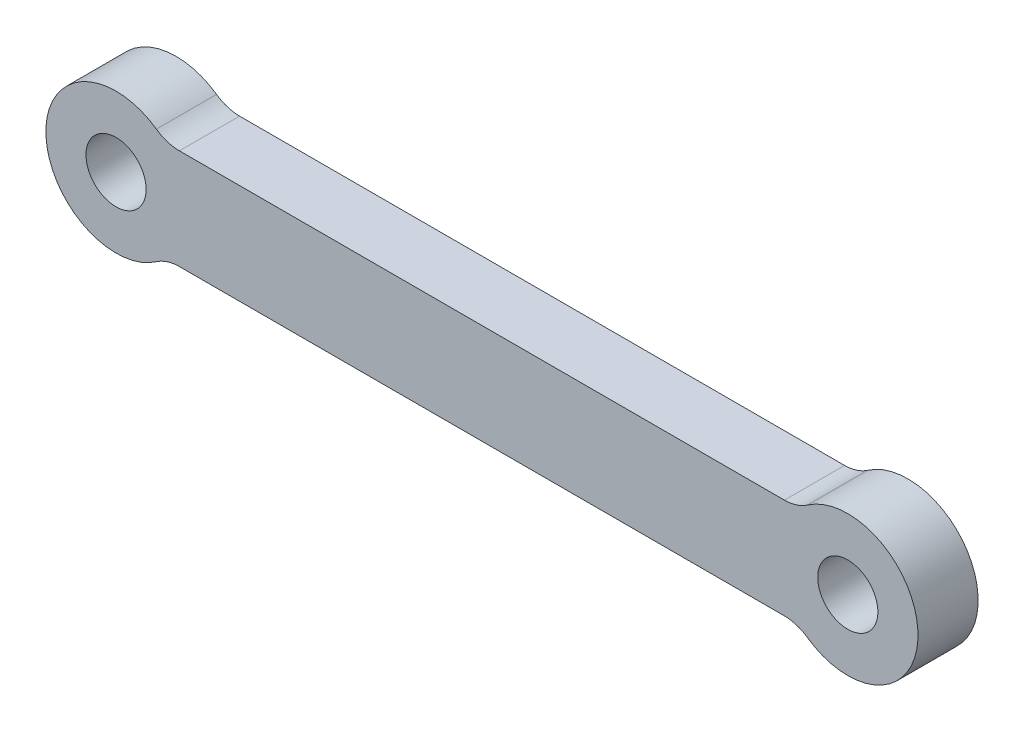
SolidWorks part; units mm, degrees
ref_plane "前视基准面" through (0, 0, 0) normal (0, 0, 1) x (1, 0, 0)
ref_plane "上视基准面" through (0, 0, 0) normal (0, 1, 0) x (1, 0, 0)
ref_plane "右视基准面" through (0, 0, 0) normal (1, 0, 0) x (0, 0, -1)
sketch "草图1" plane through (0, 0, 0) normal (0, 0, 1) x (1, 0, 0)
  line L0 (-11.7237, 0) -> (31.9737, 0) construction
  line L1 (18.25, 3.902) -> (18.25, -4.7147) construction
  line L2 (3.1623, 2.5) -> (33.3377, 2.5)
  line L3 (3.1623, -2.5) -> (33.3377, -2.5)
  circle A0 centre (0, 0) radius 1.5
  circle A1 centre (36.5, 0) radius 1.5
  arc A2 (2.0124, 2.8636) -> (2.0124, -2.8636) centre (0, 0) ccw
  arc A3 (34.4876, 2.8636) -> (34.4876, -2.8636) centre (36.5, 0) cw
  arc A4 (33.3377, -2.5) -> (34.4876, -2.8636) centre (33.3377, -4.5) cw
  arc A5 (3.1623, -2.5) -> (2.0124, -2.8636) centre (3.1623, -4.5) ccw
  arc A6 (34.4876, 2.8636) -> (33.3377, 2.5) centre (33.3377, 4.5) cw
  arc A7 (3.1623, 2.5) -> (2.0124, 2.8636) centre (3.1623, 4.5) cw
  point P17 (34.0505, -2.5)
  point P20 (2.4495, -2.5)
  point P23 (34.0505, 2.5)
  point P26 (2.4495, 2.5)
  dimension "D1" = 3
  dimension "D2" = 36.5
  dimension "D3" = 7
  dimension "D4" = 2
  dimension "D5" = 5
extrude "凸台-拉伸1" add sketch "草图1" along normal blind 3
